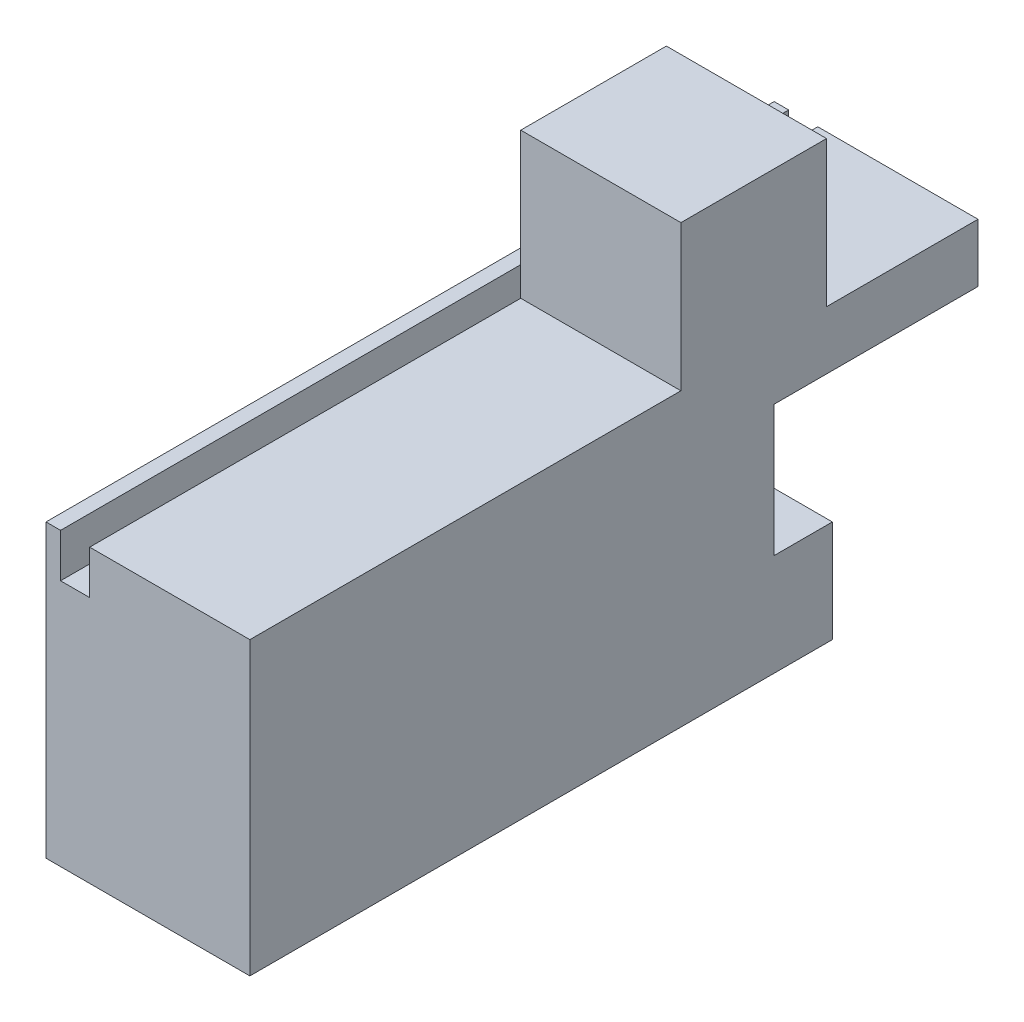
SolidWorks part; units mm, degrees
ref_plane "Front Plane" through (0, 0, 0) normal (0, 0, 1) x (1, 0, 0)
ref_plane "Top Plane" through (0, 0, 0) normal (0, 1, 0) x (1, 0, 0)
ref_plane "Right Plane" through (0, 0, 0) normal (1, 0, 0) x (0, 0, -1)
sketch "Sketch1" plane through (0, 0, 0) normal (0, 0, 1) x (1, 0, 0)
  line L0 (0, 0) -> (2, 0)
  line L1 (2, 0) -> (2, 3)
  line L2 (2, 3) -> (3, 3)
  line L3 (3, 3) -> (3, -1)
  line L4 (3, -1) -> (-1, -1)
  line L5 (-1, -1) -> (-1, 3)
  line L6 (-1, 3) -> (0, 3)
  line L7 (0, 3) -> (0, 0)
  dimension "D1" = 2
  dimension "D2" = 3
  dimension "D3" = 4
  dimension "D4" = 4
  dimension "D5" = 1
  dimension "D6" = 4
extrude "Boss-Extrude1" add sketch "Sketch1" along normal blind 50
sketch "Sketch2" plane through (3, 0, 0) normal (1, 0, 0) x (0, 0, -1)
  line L1 (-50, 3) -> (0, 3)
  line L2 (-50, 3) -> (-50, -1)
  line L3 (-50, -1) -> (0, -1)
  line L4 (0, 3) -> (0, -1)
extrude "Boss-Extrude2" add sketch "Sketch2" along normal blind 10
sketch "Sketch4" plane through (0, -1, 0) normal (0, -1, 0) x (1, 0, 0)
  line L0 (13, 50) -> (13, 0) construction
  line L1 (-1, 50) -> (13, 50)
  line L2 (-1, 50) -> (-1, 14)
  line L3 (-1, 14) -> (13, 14)
  line L4 (13, 50) -> (13, 14)
  dimension "D1" = 36
extrude "Boss-Extrude3" add sketch "Sketch4" along normal blind 16
sketch "Sketch5" plane through (0, 0, 14) normal (0, 0, -1) x (-1, 0, 0)
  line L0 (1, -17) -> (1, -1) construction
  line L1 (-13, -17) -> (1, -17)
  line L2 (-13, -17) -> (-13, -10)
  line L3 (-13, -10) -> (1, -10)
  line L4 (1, -17) -> (1, -10)
  dimension "D1" = 7
extrude "Boss-Extrude4" add sketch "Sketch5" along normal blind 4
sketch "Sketch6" plane through (13, 0, 0) normal (1, 0, 0) x (0, 0, -1)
  line L0 (0, -1) -> (0, 3) construction
  line L1 (0, 3) -> (-50, 3) construction
  circle A0 centre (-15.4, 10.1) radius 0.4
  dimension "D1" = 0.8
  dimension "D2" = 15.4
  dimension "D3" = 7.1
sketch "Sketch7" plane through (13, 0, 0) normal (1, 0, 0) x (0, 0, -1)
  line L0 (-20.4, 10.1) -> (-10.4, 10.1) construction
  line L1 (-15.4, 10.1) -> (-15.4, 3) construction
  line L2 (0, 3) -> (-50, 3) construction
  line L3 (-15.4, 10.1) -> (-15.4, 13) construction
  line L4 (-20.4, 3) -> (-20.4, 13)
  line L5 (-20.4, 13) -> (-10.4, 13)
  line L6 (-10.4, 13) -> (-10.4, 3)
  line L7 (-10.4, 3) -> (-20.4, 3)
  point P4 (-15.4, 10.1)
  dimension "D1" = 2.9
  dimension "D2" = 10
extrude "Boss-Extrude5" add sketch "Sketch7" against normal up to surface (11 mm away) up to face at (2, 1.5, 25)
sketch "Sketch8" plane through (2, 0, 0) normal (-1, 0, 0) x (0, 0, 1)
  line L0 (0, 3) -> (0, -1) construction
  line L1 (50, 3) -> (0, 3) construction
  circle A0 centre (15.4, 10.1) radius 0.4
  dimension "D1" = 0.8
  dimension "D2" = 15.4
  dimension "D3" = 7.1
extrude "Cut-Extrude2" cut sketch "Sketch8" against normal blind 7
